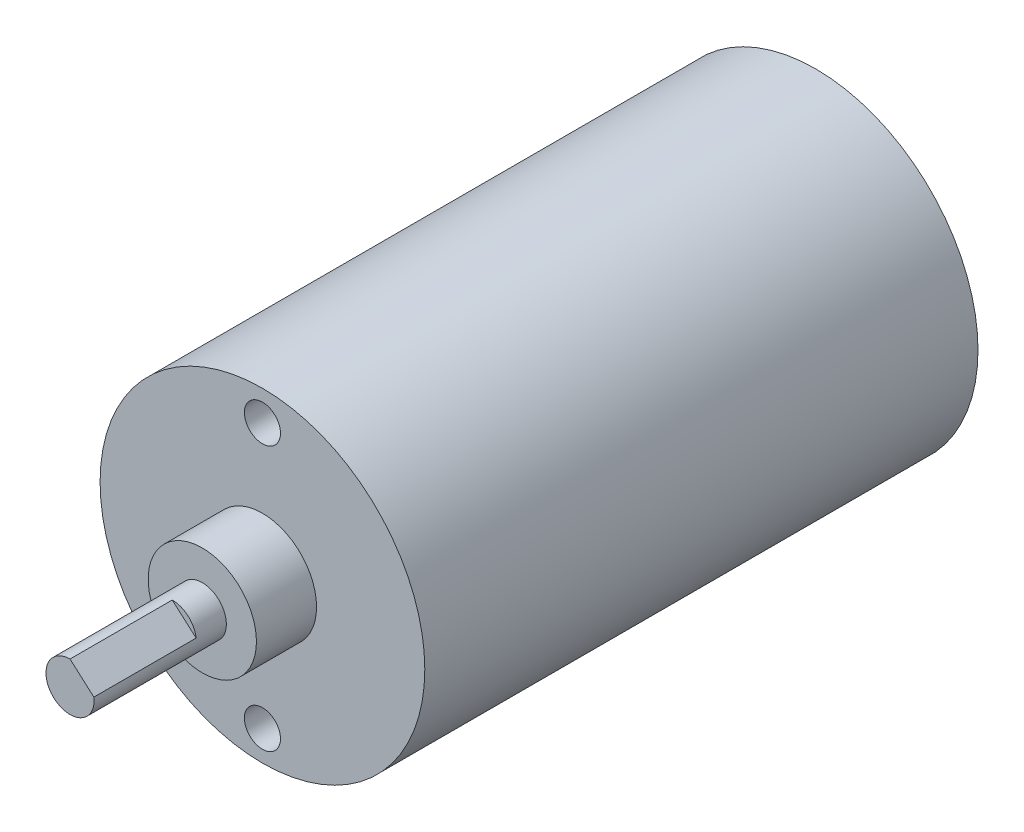
SolidWorks part; units mm, degrees
ref_plane "Piano frontale" through (0, 0, 0) normal (0, 0, 1) x (1, 0, 0)
ref_plane "Piano superiore" through (0, 0, 0) normal (0, 1, 0) x (1, 0, 0)
ref_plane "Piano destro" through (0, 0, 0) normal (1, 0, 0) x (0, 0, -1)
sketch "Schizzo1" plane through (0, 0, 0) normal (0, 0, 1) x (1, 0, 0)
  circle A0 centre (0, 0) radius 13.5
  dimension "D1" = 27
extrude "Estrusione-Estrusione1" add sketch "Schizzo1" along normal blind 46
sketch "Schizzo2" plane through (0, 0, 46) normal (0, 0, 1) x (1, 0, 0)
  circle A0 centre (0, 0) radius 4.5
  dimension "D1" = 9
extrude "Estrusione-Estrusione2" add sketch "Schizzo2" along normal blind 5
sketch "Schizzo4" plane through (0, 0, 51) normal (0, 0, 1) x (1, 0, 0)
  circle A0 centre (0, 0) radius 2
  dimension "D1" = 4
extrude "Estrusione-Estrusione3" add sketch "Schizzo4" along normal blind 2.5
sketch "Schizzo5" plane through (0, 0, 53.5) normal (0, 0, 1) x (1, 0, 0)
  line L0 (0, 2) -> (1.9843, 0.25)
  circle A0 centre (0, 0) radius 2
  circle M2 centre (0, 0) radius 2
  dimension "D1" = 1.5
extrude "Estrusione-Estrusione4" add sketch "Schizzo5" along normal blind 8.5 contours L0 M2
sketch "Schizzo6" plane through (0, 0, 46) normal (0, 0, 1) x (1, 0, 0)
  circle A2 centre (0, 11) radius 1.5
  circle A3 centre (0, -11) radius 1.5
  point P4 (0, 0)
  point P7 (0, 0)
  dimension "D1" = 3
  dimension "D2" = 3
  dimension "D3" = 11
  dimension "D4" = 11
extrude "Taglio-Estrusione1" cut sketch "Schizzo6" against normal blind 10
